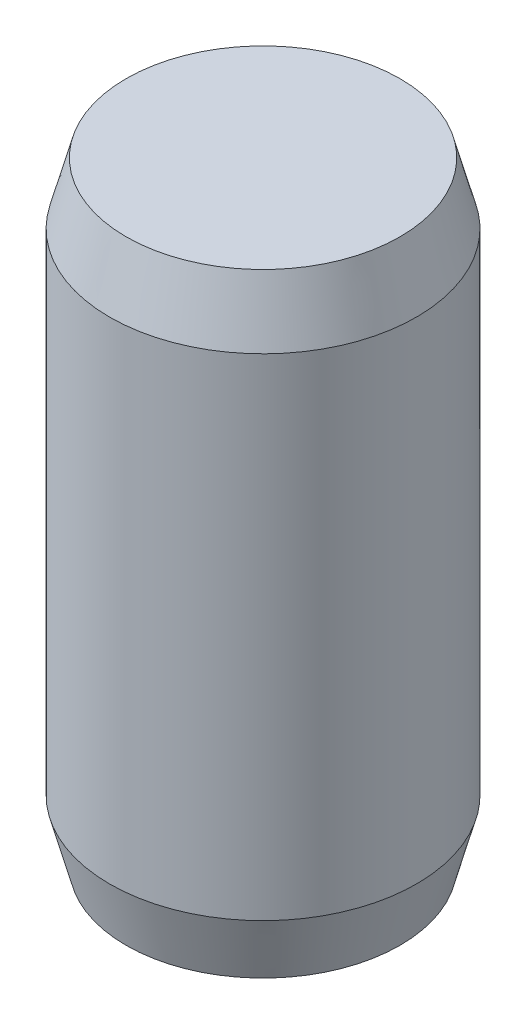
SolidWorks part; units mm, degrees
ref_plane "Front Plane" through (0, 0, 0) normal (0, 0, 1) x (1, 0, 0)
ref_plane "Top Plane" through (0, 0, 0) normal (0, 1, 0) x (1, 0, 0)
ref_plane "Right Plane" through (0, 0, 0) normal (1, 0, 0) x (0, 0, -1)
sketch "Sketch1" plane through (0, 0, 0) normal (0, 1, 0) x (1, 0, 0)
  circle A0 centre (0, 0) radius 5
  dimension "D1" = 10
extrude "Boss-Extrude1" add sketch "Sketch1" along normal blind 20
chamfer "Chamfer1" distance 2 angle 15 1 edges at (0, 20, 5)
chamfer "Chamfer2" distance 2 angle 15 1 edges at (0, 0, 5)
